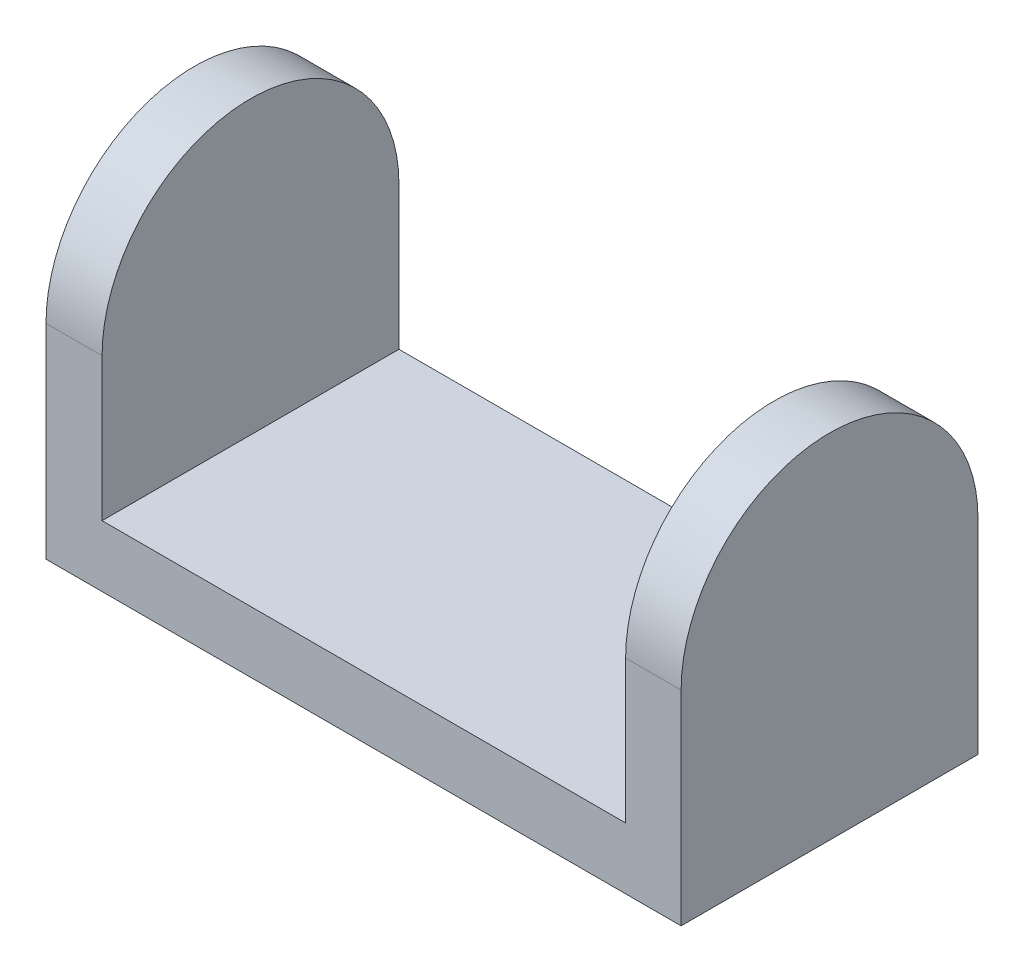
SolidWorks part; units mm, degrees
ref_plane "Plan de face" through (0, 0, 0) normal (0, 0, 1) x (1, 0, 0)
ref_plane "Plan de dessus" through (0, 0, 0) normal (0, 1, 0) x (1, 0, 0)
ref_plane "Plan de droite" through (0, 0, 0) normal (1, 0, 0) x (0, 0, -1)
sketch "Esquisse1" plane through (0, 0, 0) normal (0, 1, 0) x (1, 0, 0)
  line L1 (26.9, 12.575) -> (-26.9, 12.575)
  line L2 (26.9, 12.575) -> (26.9, -12.575)
  line L3 (26.9, -12.575) -> (-26.9, -12.575)
  line L4 (-26.9, 12.575) -> (-26.9, -12.575)
  line L5 (26.9, 12.575) -> (-26.9, -12.575) construction
  line L6 (26.9, -12.575) -> (-26.9, 12.575) construction
  point P0 (0, 0)
  dimension "D1" = 25.15
  dimension "D2" = 53.8
extrude "Boss.-Extru.1" add sketch "Esquisse1" along normal blind 5.2
sketch "Esquisse2" plane through (0, 5.2, 0) normal (0, 1, 0) x (1, 0, 0)
  line L0 (-26.9, 12.575) -> (-26.9, -12.575)
  line L1 (-26.9, 12.575) -> (-22.15, 12.575)
  line L2 (-26.9, -12.575) -> (-22.15, -12.575)
  line L3 (-22.15, 12.575) -> (-22.15, -12.575)
  dimension "D1" = 4.75
extrude "Boss.-Extru.2" add sketch "Esquisse2" along normal blind 12.1
sketch "Esquisse3" plane through (-26.9, 0, 0) normal (-1, 0, 0) x (0, 0, 1)
  line L0 (-12.575, 17.3) -> (12.575, 17.3) construction
  line L1 (12.575, 17.3) -> (12.575, 0) construction
  line L2 (12.575, 17.3) -> (-12.575, 17.3)
  arc A0 (-12.575, 17.3) -> (12.575, 17.3) centre (0, 17.3) cw
  point P8 (-12.6, 17.3)
extrude "Boss.-Extru.3" add sketch "Esquisse3" against normal up to vertex
sketch "Esquisse4" plane through (0, 5.2, 0) normal (0, 1, 0) x (1, 0, 0)
  line L0 (26.9, 12.575) -> (26.9, -12.575)
  line L3 (26.9, 12.575) -> (22.2, 12.575)
  line L4 (26.9, -12.575) -> (22.2, -12.575)
  line L5 (22.2, 12.575) -> (22.2, -12.575)
  dimension "D1" = 4.7
extrude "Boss.-Extru.4" add sketch "Esquisse4" along normal blind 12.1
sketch "Esquisse5" plane through (26.9, 0, 0) normal (1, 0, 0) x (0, 0, -1)
  line L0 (-12.575, 17.3) -> (12.575, 17.3) construction
  line L1 (12.575, 17.3) -> (-12.575, 17.3)
  arc A0 (12.575, 17.3) -> (-12.575, 17.3) centre (0, 17.3) ccw
extrude "Boss.-Extru.5" add sketch "Esquisse5" against normal up to vertex contours A0 L1
